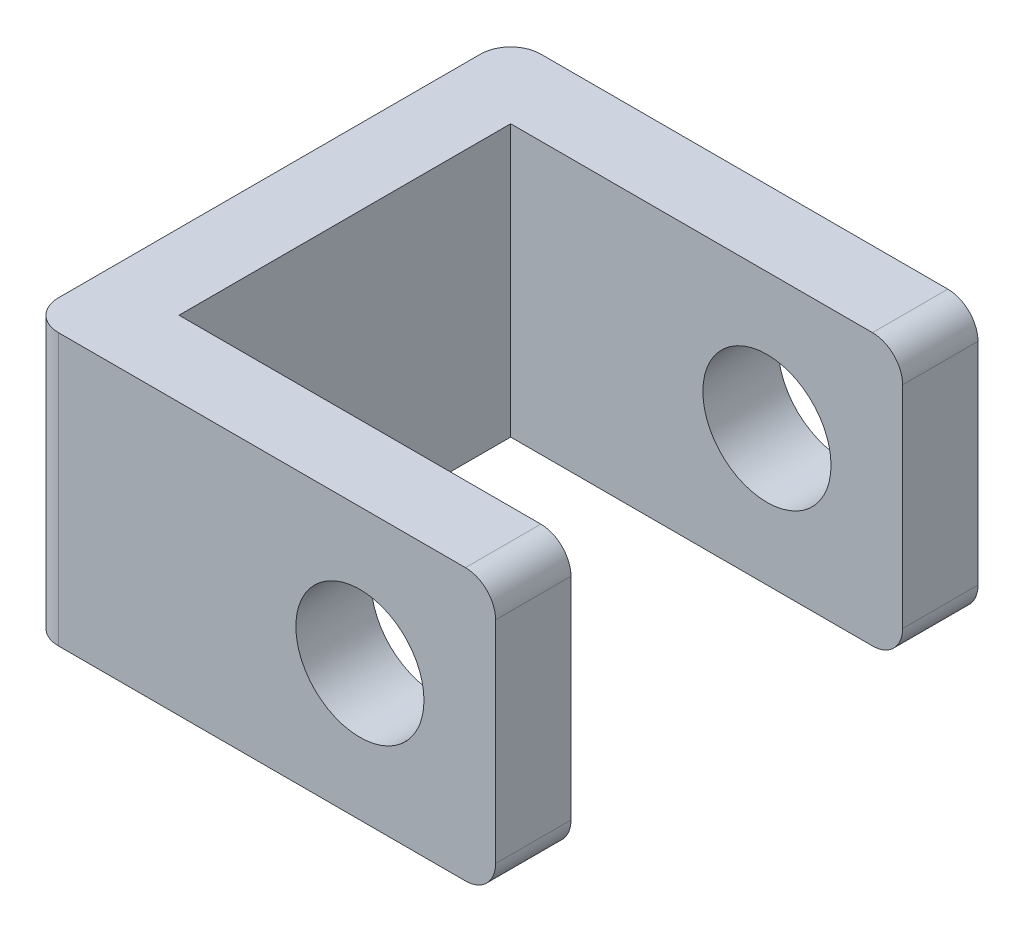
SolidWorks part; units mm, degrees
ref_plane "Спереди" through (0, 0, 0) normal (0, 0, 1) x (1, 0, 0)
ref_plane "Сверху" through (0, 0, 0) normal (0, 1, 0) x (1, 0, 0)
ref_plane "Справа" through (0, 0, 0) normal (1, 0, 0) x (0, 0, -1)
sketch "Эскиз1" plane through (0, 0, 0) normal (0, 1, 0) x (1, 0, 0)
  line L0 (0, 14) -> (0, -14)
  line L1 (2, -16) -> (31, -16)
  line L2 (31, -16) -> (31, -11)
  line L3 (31, -11) -> (5, -11)
  line L4 (5, -11) -> (5, 11)
  line L5 (5, 11) -> (31, 11)
  line L6 (31, 11) -> (31, 16)
  line L7 (31, 16) -> (2, 16)
  arc A0 (2, -16) -> (0, -14) centre (2, -14) cw
  arc A1 (0, 14) -> (2, 16) centre (2, 14) cw
  point P11 (0, -16)
  point P14 (0, 16)
  dimension "D6" = 2
  dimension "D1" = 32
  dimension "D2" = 5
  dimension "D3" = 5
  dimension "D4" = 31
  dimension "D5" = 16
extrude "Бобышка-Вытянуть1" add sketch "Эскиз1" along normal blind 18
fillet "Скругление1" radius 2 4 edges at (31, 0, 13.5) (31, 0, -13.5) (31, 18, -13.5) (31, 18, 13.5)
sketch "Эскиз2" plane through (0, 0, 16) normal (0, 0, 1) x (1, 0, 0)
  line L0 (31, 16) -> (31, 2) construction
  line L1 (2, 0) -> (29, 0) construction
  circle A0 centre (22, 9) radius 4.25
  point P2 (31, 9)
  dimension "D1" = 8.5
  dimension "D2" = 9
  dimension "D3" = 9
extrude "Вырез-Вытянуть1" cut sketch "Эскиз2" against normal through all
